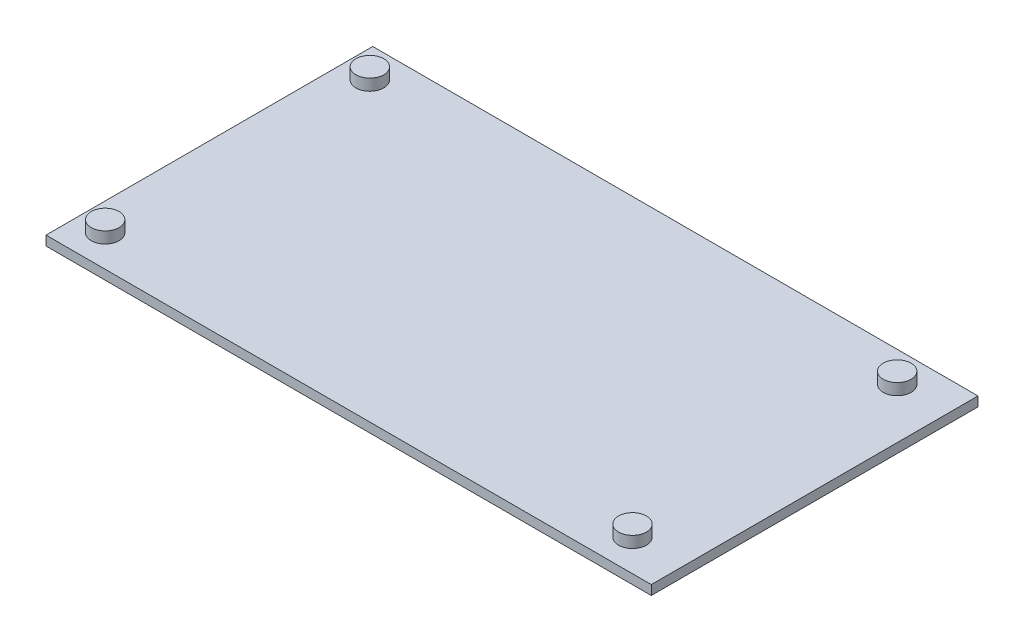
SolidWorks part; units mm, degrees
ref_plane "Front Plane" through (0, 0, 0) normal (0, 0, 1) x (1, 0, 0)
ref_plane "Top Plane" through (0, 0, 0) normal (0, 1, 0) x (1, 0, 0)
ref_plane "Right Plane" through (0, 0, 0) normal (1, 0, 0) x (0, 0, -1)
sketch "Sketch1" plane through (0, -1, 0) normal (0, -1, 0) x (1, 0, 0)
  line L1 (0, -1.815) -> (0, 1.815) construction
  line L2 (-47.8, 61.8) -> (47.8, 61.8)
  line L3 (-47.8, 61.8) -> (-47.8, 10.2)
  line L4 (-47.8, 10.2) -> (47.8, 10.2)
  line L5 (47.8, 61.8) -> (47.8, 10.2)
  line L7 (48, 62) -> (-48, 62) construction
  line L8 (-48, 62) -> (-48, 10) construction
  line L9 (-48, 10) -> (48, 10) construction
  point P4 (0, 61.8)
  dimension "D1" = 0.2
  dimension "D2" = 0.2
  dimension "D3" = 0.2
extrude "Boss-Extrude1" add sketch "Sketch1" along normal offset from surface (1.5 mm away) 0.5
sketch "Sketch2" plane through (0, -1, 0) normal (0, 1, 0) x (1, 0, 0)
  circle A0 centre (-43.4539, -56.8) radius 2.2
  circle A1 centre (-43.4539, -15) radius 2.2
  circle A2 centre (39.8328, -15) radius 2.2
  circle A3 centre (39.8328, -56.8) radius 2.2
  dimension "D1" = 4.4
  dimension "D2" = 4.4
  dimension "D3" = 4.4
  dimension "D4" = 4.4
extrude "Boss-Extrude2" add sketch "Sketch2" along normal offset from surface (1.8 mm away) 2.2
